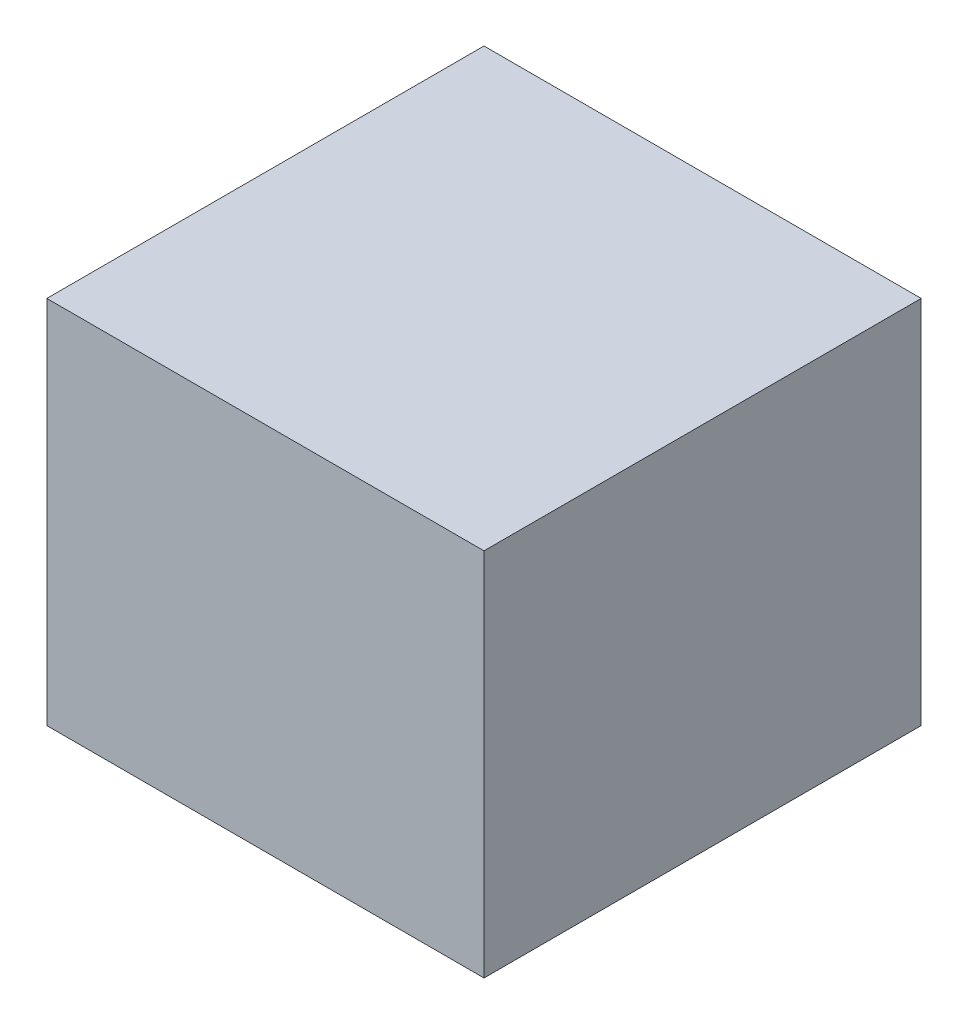
SolidWorks part; units mm, degrees
ref_plane "Front Plane" through (0, 0, 0) normal (0, 0, 1) x (1, 0, 0)
ref_plane "Top Plane" through (0, 0, 0) normal (0, 1, 0) x (1, 0, 0)
ref_plane "Right Plane" through (0, 0, 0) normal (1, 0, 0) x (0, 0, -1)
sketch "Sketch1" plane through (0, 0, 0) normal (0, 1, 0) x (1, 0, 0)
  line L1 (-20.4775, 155.5012) -> (309.7225, 155.5012)
  line L2 (-20.4775, 155.5012) -> (-20.4775, -174.6988)
  line L3 (-20.4775, -174.6988) -> (309.7225, -174.6988)
  line L4 (309.7225, 155.5012) -> (309.7225, -174.6988)
  dimension "D1" = 330.2
  dimension "D2" = 330.2
extrude "Boss-Extrude1" add sketch "Sketch1" along normal blind 279.4
